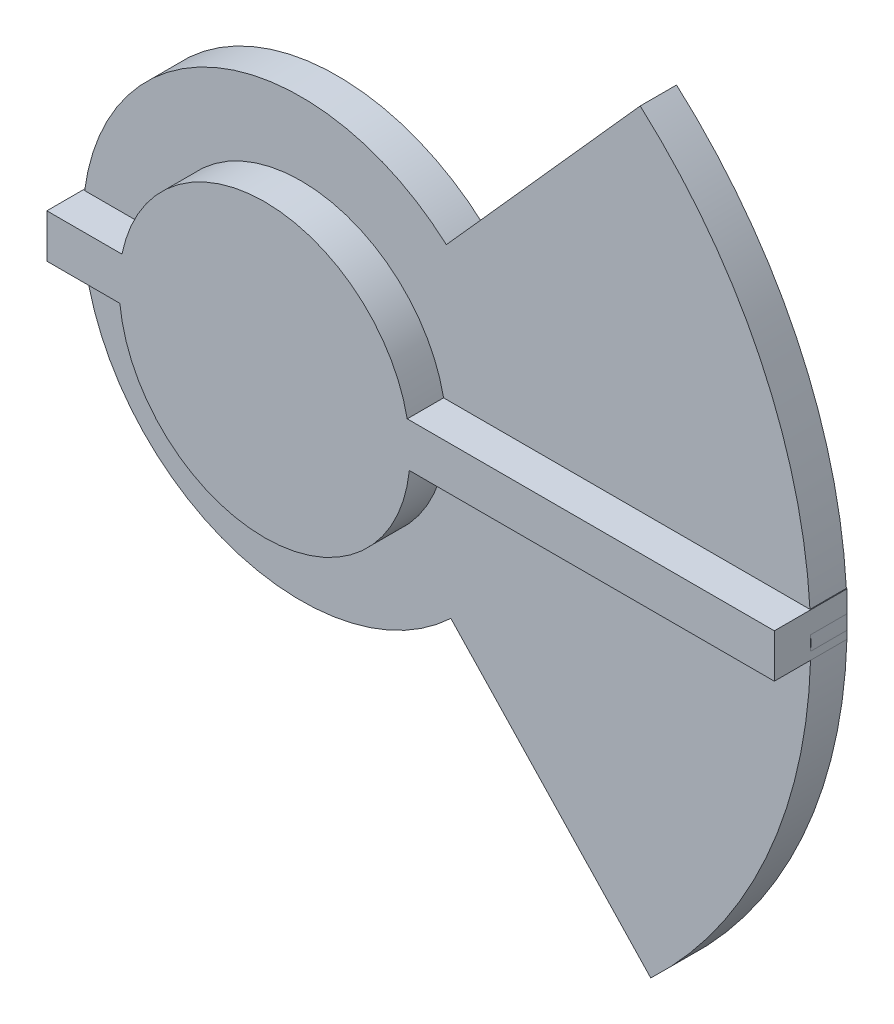
SolidWorks part; units mm, degrees
ref_plane "Front Plane" through (0, 0, 0) normal (0, 0, 1) x (1, 0, 0)
ref_plane "Top Plane" through (0, 0, 0) normal (0, 1, 0) x (1, 0, 0)
ref_plane "Right Plane" through (0, 0, 0) normal (1, 0, 0) x (0, 0, -1)
sketch "Sketch3" plane through (0, 0, 0) normal (0, 0, 1) x (1, 0, 0)
  line L2 (-4.165, 23.8738) -> (19.3918, 59.8282)
  line L3 (49.464, 2.7315) -> (-50.536, 2.7315)
  line L4 (49.464, 2.7315) -> (49.464, -3.2685)
  line L5 (49.464, -3.2685) -> (-50.536, -3.2685)
  line L6 (-50.536, 2.7315) -> (-50.536, -3.2685)
  line L7 (49.464, 2.7315) -> (-50.536, -3.2685) construction
  line L8 (49.464, -3.2685) -> (-50.536, 2.7315) construction
  line L9 (2.7988, -19.9873) -> (34.7967, -45.6453)
  circle A6 centre (-20.606, -1.2199) radius 30
  circle A7 centre (-20.606, -1.2199) radius 20
  arc A8 (19.3918, 59.8282) -> (34.7967, -45.6453) centre (-26.5842, -0.7486) cw
  arc A9 (-4.165, 23.8738) -> (2.7988, -19.9873) centre (-20.606, -1.2199) cw
  point P3 (-0.536, -0.2685)
  dimension "D1" = 60
  dimension "D2" = 40
  dimension "D3" = 6
  dimension "D4" = 100
extrude "Boss-Extrude3" add sketch "Sketch3" along normal blind 10 contours L3 A7
sketch "Sketch5" plane through (0, 0, 0) normal (0, 0, 1) x (1, 0, 0)
  line L0 (-0.6227, 21.1557) -> (26.0217, 50.9898)
  line L1 (0, -23.0234) -> (27.4747, -52.0948)
  line L2 (49.464, 2.7315) -> (49.464, -3.2685) construction
  circle A0 centre (-20.606, -1.2199) radius 30
  arc A1 (26.0217, 50.9898) -> (27.4747, -52.0948) centre (-20.3687, -1.2166) cw
  arc A2 (-0.6227, 21.1557) -> (0, -23.0234) centre (-20.606, -1.2199) cw
  point P9 (49.464, -0.2323)
  point P12 (49.464, -0.2685)
  dimension "D1" = 40
  dimension "D2" = 0
extrude "Boss-Extrude4" add sketch "Sketch5" along normal blind 5 contours A1 L0 A0 L1 | A0
